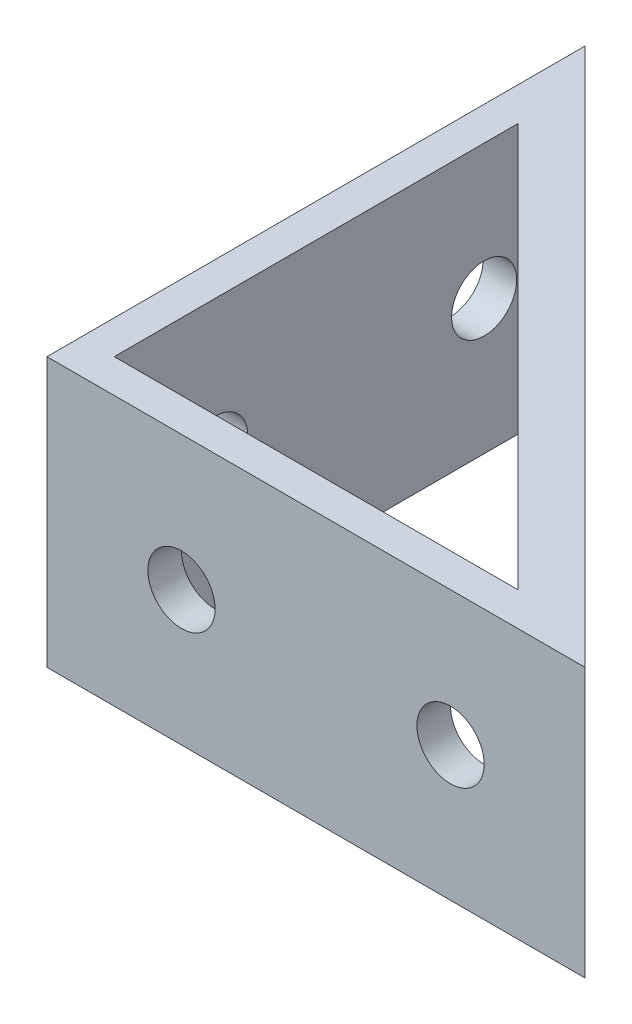
SolidWorks part; units mm, degrees
material "6061 Alloy"
ref_plane "Front Plane" through (0, 0, 0) normal (0, 0, 1) x (1, 0, 0)
ref_plane "Top Plane" through (0, 0, 0) normal (0, 1, 0) x (1, 0, 0)
ref_plane "Right Plane" through (0, 0, 0) normal (1, 0, 0) x (0, 0, -1)
sketch "Sketch1" plane through (0, 0, 0) normal (0, 1, 0) x (1, 0, 0)
  line L0 (0, 0) -> (0, 50.8)
  line L1 (0, 50.8) -> (50.8, 0)
  line L2 (50.8, 0) -> (0, 0)
  line L3 (3.175, 3.175) -> (3.175, 41.275)
  line L4 (3.175, 41.275) -> (41.275, 3.175)
  line L5 (41.275, 3.175) -> (3.175, 3.175)
  dimension "D1" = 50.8
  dimension "D2" = 50.8
  dimension "D3" = 38.1
  dimension "D4" = 3.175
  dimension "1/8" = 3.175
extrude "Boss-Extrude1" add sketch "Sketch1" along normal blind 25.4
hole_wizard "C (0.242) Diameter Hole1" positions "Sketch3" profile "Sketch2" hole size "C" standard "ANSI Inch" end condition through all
sketch "Sketch3" plane through (0, 0, 0) normal (-1, 0, 0) x (0, 0, 1)
  line L0 (-50.8, 25.4) -> (-50.8, 0) construction
  line L1 (0, 25.4) -> (0, 0) construction
  point P2 (-12.7, 12.7)
  point P11 (-38.1, 12.7)
  dimension "D1" = 12.7
  dimension "D2" = 12.7
sketch "Sketch2" plane through (0, 12.7, -12.7) normal (0, 1, 0) x (0, 0, 1)
  line L0 (0, 0) -> (0, 50.8)
  line L1 (0, 50.8) -> (3.0734, 50.8)
  line L2 (3.0734, 50.8) -> (3.0734, 0)
  line L5 (3.0734, 0) -> (0, 0)
  line L11 (0, -6.35) -> (0, 107.95) construction
  dimension "Thru Hole Dia." = 6.1468
  dimension "Thru Hole Depth" = 50.8
hole_wizard "1/4 (0.25) Diameter Hole1" positions "Sketch5" profile "Sketch4" hole size "1/4" standard "ANSI Inch" end condition through all
sketch "Sketch5" plane through (0, 0, 0) normal (0, 0, 1) x (1, 0, 0)
  line L0 (50.8, 25.4) -> (50.8, 0) construction
  line L1 (0, 25.4) -> (0, 0) construction
  point P0 (38.1, 12.7)
  point P2 (12.7, 12.7)
  dimension "D1" = 12.7
  dimension "D2" = 12.7
sketch "Sketch4" plane through (38.1, 12.7, 0) normal (1, 0, 0) x (0, -1, 0)
  line L0 (0, 0) -> (0, 50.8)
  line L1 (0, 50.8) -> (3.175, 50.8)
  line L2 (3.175, 50.8) -> (3.175, 0)
  line L5 (3.175, 0) -> (0, 0)
  line L11 (0, -6.35) -> (0, 107.95) construction
  dimension "Thru Hole Dia." = 6.35
  dimension "Thru Hole Depth" = 50.8
